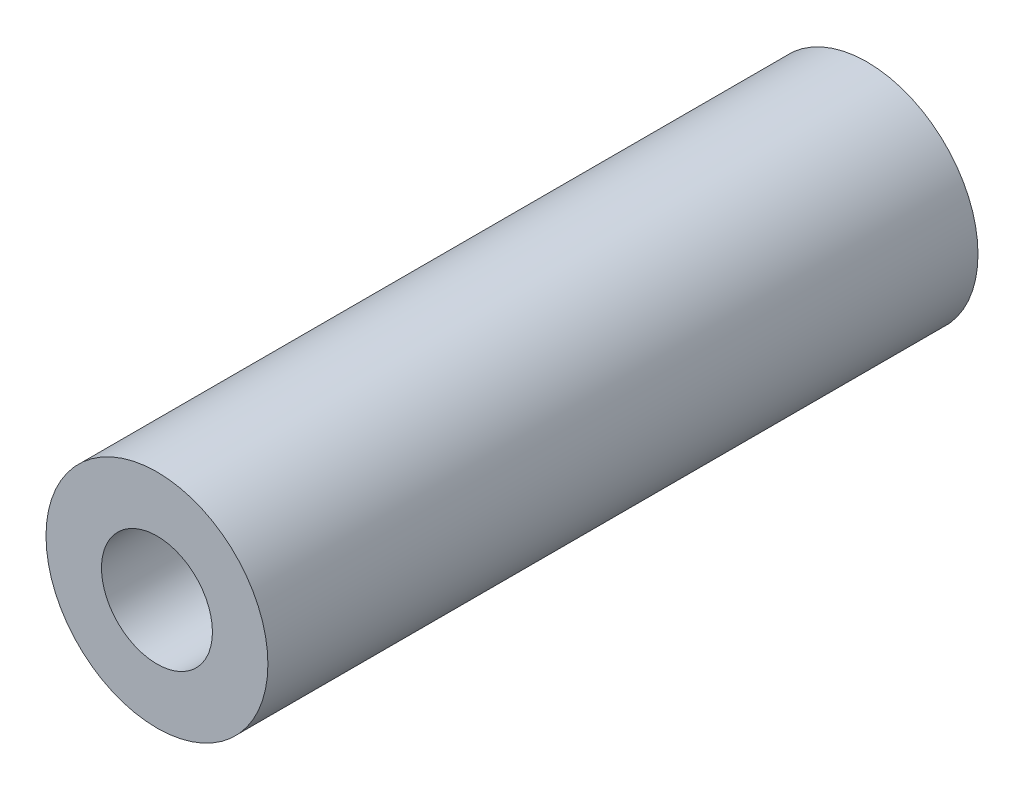
SolidWorks part; units mm, degrees
ref_plane "Front Plane" through (0, 0, 0) normal (0, 0, 1) x (1, 0, 0)
ref_plane "Top Plane" through (0, 0, 0) normal (0, 1, 0) x (1, 0, 0)
ref_plane "Right Plane" through (0, 0, 0) normal (1, 0, 0) x (0, 0, -1)
sketch "Sketch2" plane through (0, 0, 0) normal (0, 0, 1) x (1, 0, 0)
  circle A0 centre (0, 0) radius 2.5
  circle A1 centre (0, 0) radius 1.25
  dimension "D1" = 2.5
  dimension "D2" = 5
extrude "Boss-Extrude1" add sketch "Sketch2" against normal blind 16
